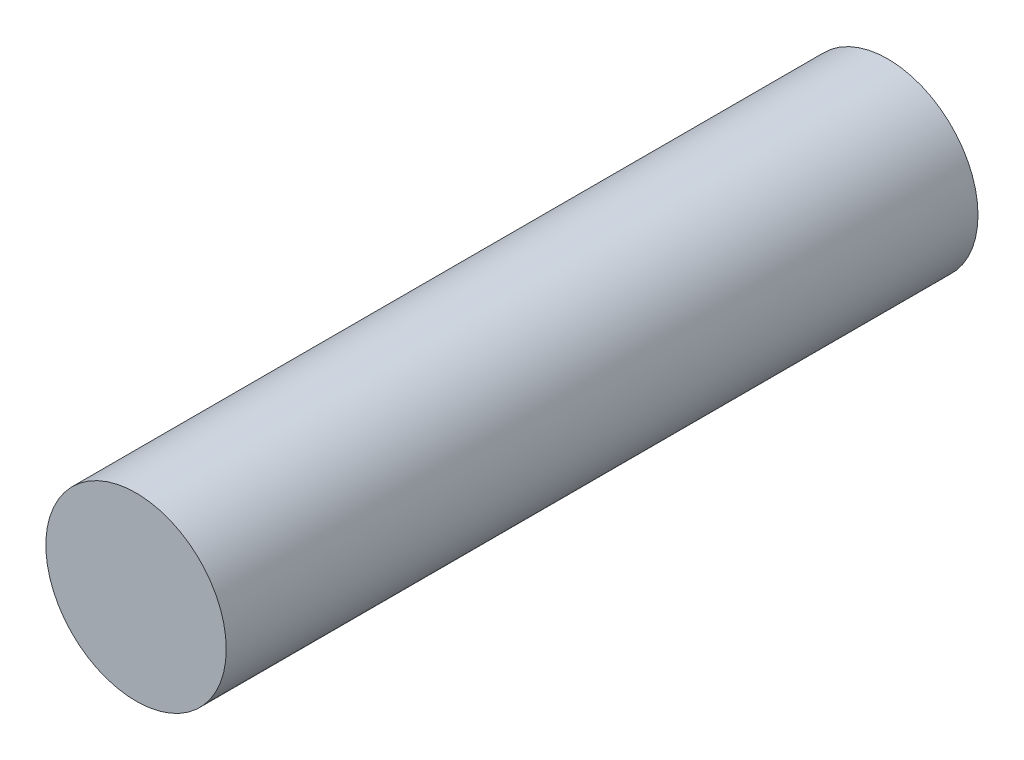
SolidWorks part; units mm, degrees
ref_plane "Front Plane" through (0, 0, 0) normal (0, 0, 1) x (1, 0, 0)
ref_plane "Top Plane" through (0, 0, 0) normal (0, 1, 0) x (1, 0, 0)
ref_plane "Right Plane" through (0, 0, 0) normal (1, 0, 0) x (0, 0, -1)
sketch "Sketch1" plane through (0, 0, 0) normal (0, 0, 1) x (1, 0, 0)
  circle A0 centre (0, 0) radius 2.5
  dimension "D1" = 5
extrude "Boss-Extrude1" add sketch "Sketch1" along normal mid plane 20
other "Move Face1" face at (2.5, 0, 10) parameters "D1"=0.1
